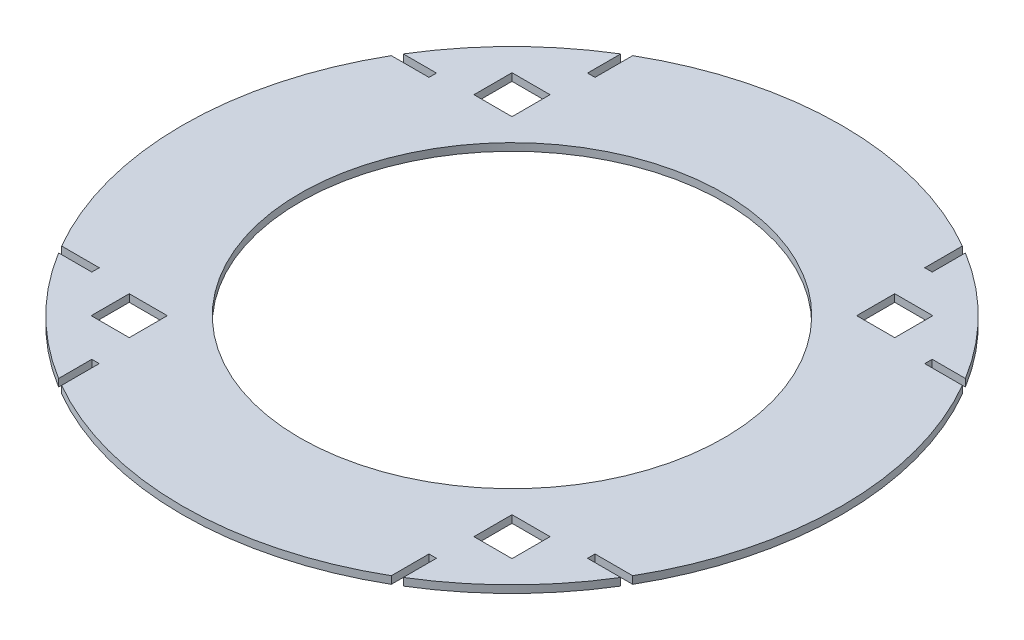
SolidWorks part; units mm, degrees
ref_plane "Front Plane" through (0, 0, 0) normal (0, 0, 1) x (1, 0, 0)
ref_plane "Top Plane" through (0, 0, 0) normal (0, 1, 0) x (1, 0, 0)
ref_plane "Right Plane" through (0, 0, 0) normal (1, 0, 0) x (0, 0, -1)
sketch "Sketch1" plane through (0, 0, 0) normal (0, 1, 0) x (1, 0, 0)
  line L0 (115, 140.4) -> (115, 115)
  line L1 (-140.4, 140.4) -> (140.4, 140.4) construction
  line L2 (-140.4, 140.4) -> (-140.4, -140.4) construction
  line L3 (-140.4, -140.4) -> (140.4, -140.4) construction
  line L4 (140.4, 140.4) -> (140.4, -140.4) construction
  line L5 (0, -140.4) -> (0, 140.4) construction
  line L6 (-140.4, 0) -> (140.4, 0) construction
  line L7 (-140.4, 140.4) -> (-115, 140.4)
  line L8 (-140.4, 140.4) -> (-140.4, 115)
  line L9 (-140.4, 115) -> (-115, 115)
  line L10 (-115, 140.4) -> (-115, 115)
  line L11 (140.4, 115) -> (115, 115)
  line L12 (140.4, 140.4) -> (140.4, 115)
  line L13 (140.4, 140.4) -> (115, 140.4)
  line L14 (140.4, -140.4) -> (140.4, -115)
  line L15 (140.4, -115) -> (115, -115)
  line L16 (115, -140.4) -> (115, -115)
  line L17 (140.4, -140.4) -> (115, -140.4)
  line L18 (-115, -140.4) -> (-115, -115)
  line L19 (-140.4, -140.4) -> (-115, -140.4)
  line L20 (-140.4, -140.4) -> (-140.4, -115)
  line L21 (-140.4, -115) -> (-115, -115)
  line L22 (115, 165.4) -> (110, 165.4)
  line L23 (-115, 165.4) -> (-110, 165.4)
  line L24 (-115, 165.4) -> (-115, 187.55)
  line L25 (110, 165.4) -> (110, 190.5256)
  line L26 (-110, 165.4) -> (-110, 190.5256)
  line L27 (-165.4, 115) -> (-187.55, 115)
  line L28 (-165.4, 115) -> (-165.4, 110)
  line L29 (-165.4, 110) -> (-190.5256, 110)
  line L30 (115, 165.4) -> (115, 187.55)
  line L31 (165.4, 115) -> (165.4, 110)
  line L32 (165.4, 110) -> (190.5256, 110)
  line L33 (165.4, 115) -> (187.55, 115)
  line L34 (165.4, -110) -> (190.5256, -110)
  line L35 (165.4, -115) -> (165.4, -110)
  line L36 (165.4, -115) -> (187.55, -115)
  line L37 (115, -165.4) -> (110, -165.4)
  line L38 (115, -165.4) -> (115, -187.55)
  line L39 (110, -165.4) -> (110, -190.5256)
  line L40 (-115, -165.4) -> (-110, -165.4)
  line L41 (-110, -165.4) -> (-110, -190.5256)
  line L42 (-115, -165.4) -> (-115, -187.55)
  line L43 (-165.4, -115) -> (-165.4, -110)
  line L44 (-165.4, -110) -> (-190.5256, -110)
  line L45 (-165.4, -115) -> (-187.55, -115)
  line L47 (-100, 100) -> (100, 100) construction
  line L48 (-100, 100) -> (-100, -100) construction
  line L49 (-100, -100) -> (100, -100) construction
  line L50 (100, 100) -> (100, -100) construction
  line L51 (0, -100) -> (0, 100) construction
  line L52 (-100, 0) -> (100, 0) construction
  arc A0 (-190.5256, 110) -> (-190.5256, -110) centre (0, 0) ccw
  arc A1 (-115, 187.55) -> (-187.55, 115) centre (0, 0) ccw
  arc A2 (110, 190.5256) -> (-110, 190.5256) centre (0, 0) ccw
  arc A3 (187.55, 115) -> (115, 187.55) centre (0, 0) ccw
  arc A4 (190.5256, -110) -> (190.5256, 110) centre (0, 0) ccw
  arc A5 (115, -187.55) -> (187.55, -115) centre (0, 0) ccw
  arc A6 (-110, -190.5256) -> (110, -190.5256) centre (0, 0) ccw
  arc A7 (-187.55, -115) -> (-115, -187.55) centre (0, 0) ccw
  circle A8 centre (0, 0) radius 141.4214
  dimension "D1" = 440
  dimension "D2" = 280.8
  dimension "D3" = 25.4
  dimension "D4" = 5
  dimension "D5" = 5
  dimension "D6" = 25
  dimension "D7" = 25
  dimension "D8" = 200
extrude "Boss-Extrude1" add sketch "Sketch1" along normal blind 5
